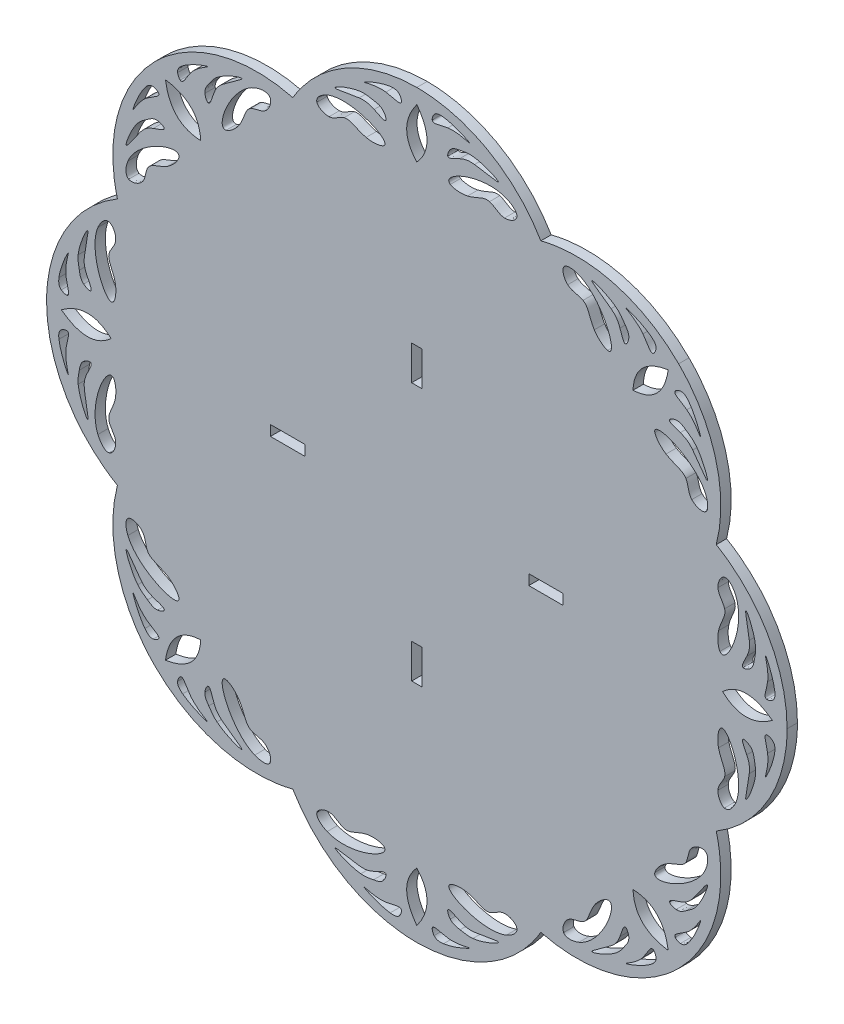
SolidWorks part; units mm, degrees
ref_plane "Plano frontal" through (0, 0, 0) normal (0, 0, 1) x (1, 0, 0)
ref_plane "Plano superior" through (0, 0, 0) normal (0, 1, 0) x (1, 0, 0)
ref_plane "Plano direito" through (0, 0, 0) normal (1, 0, 0) x (0, 0, -1)
sketch "Model" plane through (0, 0, 0) normal (0, 0, 1) x (1, 0, 0)
  line L0 (57.9546, 38.6366) -> (57.9546, 38.6367)
  line L37 (1, 34.3089) -> (1, 40.9756)
  line L38 (1, 40.9756) -> (-1, 40.9756)
  line L39 (-1, 40.9756) -> (-1, 34.3089)
  line L40 (-1, 34.3089) -> (1, 34.3089)
  line L41 (-21.6667, 63.6423) -> (-28.3333, 63.6423)
  line L42 (-28.3333, 63.6423) -> (-28.3333, 61.6423)
  line L43 (-28.3333, 61.6423) -> (-21.6667, 61.6423)
  line L44 (-21.6667, 61.6423) -> (-21.6667, 63.6423)
  line L45 (1, 84.3089) -> (1, 90.9756)
  line L46 (1, 90.9756) -> (-1, 90.9756)
  line L47 (-1, 90.9756) -> (-1, 84.3089)
  line L48 (-1, 84.3089) -> (1, 84.3089)
  line L49 (28.3333, 63.6423) -> (21.6667, 63.6423)
  line L50 (21.6667, 63.6423) -> (21.6667, 61.6423)
  line L51 (21.6667, 61.6423) -> (28.3333, 61.6423)
  line L52 (28.3333, 61.6423) -> (28.3333, 63.6423)
  spline S0 degree 3 poles (-52.251, 106.4004) (-51.0841, 107.3002) (-49.5495, 107.8231) (-50.0038, 108.419) knots 0 0 0 0 0.166667 0.166667 0.166667 0.166667
  spline S1 degree 3 poles (-50.0038, 108.419) (-50.1747, 108.6432) (-50.6272, 108.8778) (-51.0215, 108.9249) knots 0.166667 0.166667 0.166667 0.166667 0.333333 0.333333 0.333333 0.333333
  spline S2 degree 3 poles (-51.0215, 108.9249) (-51.675, 109.0029) (-52.169, 108.5658) (-52.6362, 107.9552) knots 0.333333 0.333333 0.333333 0.333333 0.5 0.5 0.5 0.5
  spline S3 degree 3 poles (-52.6362, 107.9552) (-53.9613, 106.2236) (-55.0715, 103.0965) (-54.9171, 103.125) knots 0.5 0.5 0.5 0.5 0.666667 0.666667 0.666667 0.666667
  spline S4 degree 3 poles (-54.9171, 103.125) (-54.795, 103.1474) (-53.8824, 105.1424) (-52.251, 106.4004) knots 0.666667 0.666667 0.666667 0.666667 1 1 1 1
  spline S5 degree 3 poles (-52.0754, 94.806) (-51.4239, 95.9147) (-49.6775, 96.0478) (-48.2286, 96.9769) knots 0 0 0 0 0.142857 0.142857 0.142857 0.142857
  spline S6 degree 3 poles (-48.2286, 96.9769) (-47.1297, 97.6816) (-46.2019, 98.8443) (-46.0577, 99.5288) knots 0.142857 0.142857 0.142857 0.142857 0.285714 0.285714 0.285714 0.285714
  spline S7 degree 3 poles (-46.0577, 99.5288) (-45.5709, 101.8383) (-54.0056, 98.7029) (-55.9222, 94.0062) knots 0.285714 0.285714 0.285714 0.285714 0.428571 0.428571 0.428571 0.428571
  spline S8 degree 3 poles (-55.9222, 94.0062) (-56.4255, 92.7729) (-56.4794, 91.4319) (-55.7669, 91.0417) knots 0.428571 0.428571 0.428571 0.428571 0.571429 0.571429 0.571429 0.571429
  spline S9 degree 3 poles (-55.7669, 91.0417) (-55.1261, 90.6907) (-53.8657, 91.1085) (-53.2181, 91.8352) knots 0.571429 0.571429 0.571429 0.571429 0.714286 0.714286 0.714286 0.714286
  spline S10 degree 3 poles (-53.2181, 91.8352) (-52.4459, 92.7016) (-52.5449, 94.007) (-52.0754, 94.806) knots 0.714286 0.714286 0.714286 0.714286 1 1 1 1
  spline S11 degree 3 poles (-32.1752, 114.7062) (-31.3763, 115.1757) (-30.0708, 115.0766) (-29.2044, 115.8488) knots 0 0 0 0 0.142857 0.142857 0.142857 0.142857
  spline S12 degree 3 poles (-29.2044, 115.8488) (-28.4777, 116.4964) (-28.0599, 117.757) (-28.4109, 118.3977) knots 0.142857 0.142857 0.142857 0.142857 0.285714 0.285714 0.285714 0.285714
  spline S13 degree 3 poles (-28.4109, 118.3977) (-28.8012, 119.1102) (-30.1421, 119.0563) (-31.3753, 118.553) knots 0.285714 0.285714 0.285714 0.285714 0.428571 0.428571 0.428571 0.428571
  spline S14 degree 3 poles (-31.3753, 118.553) (-36.0721, 116.6364) (-39.2076, 108.2017) (-36.898, 108.6885) knots 0.428571 0.428571 0.428571 0.428571 0.571429 0.571429 0.571429 0.571429
  spline S15 degree 3 poles (-36.898, 108.6885) (-36.2135, 108.8327) (-35.0509, 109.7605) (-34.3461, 110.8594) knots 0.571429 0.571429 0.571429 0.571429 0.714286 0.714286 0.714286 0.714286
  spline S16 degree 3 poles (-34.3461, 110.8594) (-33.417, 112.3083) (-33.2839, 114.0547) (-32.1752, 114.7062) knots 0.714286 0.714286 0.714286 0.714286 1 1 1 1
  spline S17 degree 3 poles (-43.7696, 114.8818) (-42.5116, 116.5132) (-40.5166, 117.4258) (-40.4942, 117.5479) knots 0 0 0 0 0.166667 0.166667 0.166667 0.166667
  spline S18 degree 3 poles (-40.4942, 117.5479) (-40.4657, 117.7023) (-43.5928, 116.5921) (-45.3244, 115.267) knots 0.166667 0.166667 0.166667 0.166667 0.333333 0.333333 0.333333 0.333333
  spline S19 degree 3 poles (-45.3244, 115.267) (-45.935, 114.7997) (-46.3721, 114.3058) (-46.2941, 113.6523) knots 0.333333 0.333333 0.333333 0.333333 0.5 0.5 0.5 0.5
  spline S20 degree 3 poles (-46.2941, 113.6523) (-46.247, 113.258) (-46.0124, 112.8056) (-45.7883, 112.6346) knots 0.5 0.5 0.5 0.5 0.666667 0.666667 0.666667 0.666667
  spline S21 degree 3 poles (-45.7883, 112.6346) (-45.1922, 112.1803) (-44.6694, 113.715) (-43.7696, 114.8818) knots 0.666667 0.666667 0.666667 0.666667 1 1 1 1
  spline S22 degree 3 poles (-65.3252, 54.2545) (-65.4688, 53.4561) (-65.6419, 52.7387) (-65.5496, 51.7858) knots 0 0 0 0 0.125 0.125 0.125 0.125
  spline S23 degree 3 poles (-65.5496, 51.7858) (-65.3525, 49.752) (-63.9461, 46.6455) (-63.6955, 46.8305) knots 0.125 0.125 0.125 0.125 0.25 0.25 0.25 0.25
  spline S24 degree 3 poles (-63.6955, 46.8305) (-63.4739, 46.9939) (-64.1556, 49.7294) (-64.3418, 51.4627) knots 0.25 0.25 0.25 0.25 0.375 0.375 0.375 0.375
  spline S25 degree 3 poles (-64.3418, 51.4627) (-64.4593, 52.5554) (-64.3798, 53.2498) (-63.8571, 54.3713) knots 0.375 0.375 0.375 0.375 0.5 0.5 0.5 0.5
  spline S26 degree 3 poles (-63.8571, 54.3713) (-63.4373, 55.272) (-62.7317, 56.4482) (-63.1569, 56.6336) knots 0.5 0.5 0.5 0.5 0.625 0.625 0.625 0.625
  spline S27 degree 3 poles (-63.1569, 56.6336) (-63.4116, 56.7446) (-64.0718, 56.5003) (-64.4916, 56.1539) knots 0.625 0.625 0.625 0.625 0.75 0.75 0.75 0.75
  spline S28 degree 3 poles (-64.4916, 56.1539) (-65.1055, 55.6473) (-65.205, 54.9225) (-65.3252, 54.2545) knots 0.75 0.75 0.75 0.75 1 1 1 1
  spline S29 degree 3 poles (-65.3252, 71.0071) (-65.205, 70.3391) (-65.1055, 69.6142) (-64.4916, 69.1077) knots 0 0 0 0 0.125 0.125 0.125 0.125
  spline S30 degree 3 poles (-64.4916, 69.1077) (-64.0718, 68.7613) (-63.4116, 68.517) (-63.1569, 68.628) knots 0.125 0.125 0.125 0.125 0.25 0.25 0.25 0.25
  spline S31 degree 3 poles (-63.1569, 68.628) (-62.7317, 68.8134) (-63.4373, 69.9896) (-63.8571, 70.8903) knots 0.25 0.25 0.25 0.25 0.375 0.375 0.375 0.375
  spline S32 degree 3 poles (-63.8571, 70.8903) (-64.3798, 72.0118) (-64.4593, 72.7061) (-64.3418, 73.7989) knots 0.375 0.375 0.375 0.375 0.5 0.5 0.5 0.5
  spline S33 degree 3 poles (-64.3418, 73.7989) (-64.1556, 75.5321) (-63.4739, 78.2676) (-63.6955, 78.4311) knots 0.5 0.5 0.5 0.5 0.625 0.625 0.625 0.625
  spline S34 degree 3 poles (-63.6955, 78.4311) (-63.9461, 78.616) (-65.3525, 75.5095) (-65.5496, 73.4757) knots 0.625 0.625 0.625 0.625 0.75 0.75 0.75 0.75
  spline S35 degree 3 poles (-65.5496, 73.4757) (-65.6419, 72.5229) (-65.4688, 71.8054) (-65.3252, 71.0071) knots 0.75 0.75 0.75 0.75 1 1 1 1
  spline S36 degree 3 poles (-43.7696, 10.3798) (-44.6694, 11.5466) (-45.1922, 13.0812) (-45.7883, 12.6269) knots 0 0 0 0 0.166667 0.166667 0.166667 0.166667
  spline S37 degree 3 poles (-45.7883, 12.6269) (-46.0124, 12.456) (-46.247, 12.0036) (-46.2941, 11.6093) knots 0.166667 0.166667 0.166667 0.166667 0.333333 0.333333 0.333333 0.333333
  spline S38 degree 3 poles (-46.2941, 11.6093) (-46.3721, 10.9558) (-45.935, 10.4618) (-45.3244, 9.9946) knots 0.333333 0.333333 0.333333 0.333333 0.5 0.5 0.5 0.5
  spline S39 degree 3 poles (-45.3244, 9.9946) (-43.5928, 8.6695) (-40.4657, 7.5593) (-40.4942, 7.7137) knots 0.5 0.5 0.5 0.5 0.666667 0.666667 0.666667 0.666667
  spline S40 degree 3 poles (-40.4942, 7.7137) (-40.5166, 7.8358) (-42.5116, 8.7484) (-43.7696, 10.3798) knots 0.666667 0.666667 0.666667 0.666667 1 1 1 1
  spline S41 degree 3 poles (-32.1752, 10.5553) (-33.2839, 11.2069) (-33.417, 12.9533) (-34.3461, 14.4022) knots 0 0 0 0 0.142857 0.142857 0.142857 0.142857
  spline S42 degree 3 poles (-34.3461, 14.4022) (-35.0509, 15.5011) (-36.2135, 16.4289) (-36.898, 16.5731) knots 0.142857 0.142857 0.142857 0.142857 0.285714 0.285714 0.285714 0.285714
  spline S43 degree 3 poles (-36.898, 16.5731) (-39.2076, 17.0598) (-36.0721, 8.6252) (-31.3753, 6.7085) knots 0.285714 0.285714 0.285714 0.285714 0.428571 0.428571 0.428571 0.428571
  spline S44 degree 3 poles (-31.3753, 6.7085) (-30.1421, 6.2053) (-28.8012, 6.1514) (-28.4109, 6.8639) knots 0.428571 0.428571 0.428571 0.428571 0.571429 0.571429 0.571429 0.571429
  spline S45 degree 3 poles (-28.4109, 6.8639) (-28.0599, 7.5046) (-28.4777, 8.7651) (-29.2044, 9.4128) knots 0.571429 0.571429 0.571429 0.571429 0.714286 0.714286 0.714286 0.714286
  spline S46 degree 3 poles (-29.2044, 9.4128) (-30.0708, 10.185) (-31.3763, 10.0859) (-32.1752, 10.5553) knots 0.714286 0.714286 0.714286 0.714286 1 1 1 1
  spline S47 degree 3 poles (-52.0754, 30.4556) (-52.5449, 31.2546) (-52.4459, 32.56) (-53.2181, 33.4264) knots 0 0 0 0 0.142857 0.142857 0.142857 0.142857
  spline S48 degree 3 poles (-53.2181, 33.4264) (-53.8657, 34.1531) (-55.1261, 34.5708) (-55.7669, 34.2199) knots 0.142857 0.142857 0.142857 0.142857 0.285714 0.285714 0.285714 0.285714
  spline S49 degree 3 poles (-55.7669, 34.2199) (-56.4794, 33.8296) (-56.4255, 32.4887) (-55.9222, 31.2554) knots 0.285714 0.285714 0.285714 0.285714 0.428571 0.428571 0.428571 0.428571
  spline S50 degree 3 poles (-55.9222, 31.2554) (-54.0056, 26.5587) (-45.5709, 23.4233) (-46.0577, 25.7328) knots 0.428571 0.428571 0.428571 0.428571 0.571429 0.571429 0.571429 0.571429
  spline S51 degree 3 poles (-46.0577, 25.7328) (-46.2019, 26.4173) (-47.1297, 27.5799) (-48.2286, 28.2847) knots 0.571429 0.571429 0.571429 0.571429 0.714286 0.714286 0.714286 0.714286
  spline S52 degree 3 poles (-48.2286, 28.2847) (-49.6775, 29.2138) (-51.4239, 29.3469) (-52.0754, 30.4556) knots 0.714286 0.714286 0.714286 0.714286 1 1 1 1
  spline S53 degree 3 poles (-52.251, 18.8612) (-53.8824, 20.1192) (-54.795, 22.1142) (-54.9171, 22.1366) knots 0 0 0 0 0.166667 0.166667 0.166667 0.166667
  spline S54 degree 3 poles (-54.9171, 22.1366) (-55.0715, 22.1651) (-53.9613, 19.038) (-52.6362, 17.3064) knots 0.166667 0.166667 0.166667 0.166667 0.333333 0.333333 0.333333 0.333333
  spline S55 degree 3 poles (-52.6362, 17.3064) (-52.169, 16.6958) (-51.675, 16.2587) (-51.0215, 16.3367) knots 0.333333 0.333333 0.333333 0.333333 0.5 0.5 0.5 0.5
  spline S56 degree 3 poles (-51.0215, 16.3367) (-50.6272, 16.3838) (-50.1747, 16.6183) (-50.0038, 16.8425) knots 0.5 0.5 0.5 0.5 0.666667 0.666667 0.666667 0.666667
  spline S57 degree 3 poles (-50.0038, 16.8425) (-49.5495, 17.4385) (-51.0841, 17.9613) (-52.251, 18.8612) knots 0.666667 0.666667 0.666667 0.666667 1 1 1 1
  spline S58 degree 3 poles (8.3763, -2.6943) (9.1746, -2.838) (9.8921, -3.0111) (10.8449, -2.9188) knots 0 0 0 0 0.125 0.125 0.125 0.125
  spline S59 degree 3 poles (10.8449, -2.9188) (12.8788, -2.7217) (15.9852, -1.3154) (15.8003, -1.0647) knots 0.125 0.125 0.125 0.125 0.25 0.25 0.25 0.25
  spline S60 degree 3 poles (15.8003, -1.0647) (15.6369, -0.8432) (12.9013, -1.5248) (11.1681, -1.711) knots 0.25 0.25 0.25 0.25 0.375 0.375 0.375 0.375
  spline S61 degree 3 poles (11.1681, -1.711) (10.0754, -1.8285) (9.381, -1.749) (8.2594, -1.2263) knots 0.375 0.375 0.375 0.375 0.5 0.5 0.5 0.5
  spline S62 degree 3 poles (8.2594, -1.2263) (7.3588, -0.8065) (6.1826, -0.1009) (5.9972, -0.5261) knots 0.5 0.5 0.5 0.5 0.625 0.625 0.625 0.625
  spline S63 degree 3 poles (5.9972, -0.5261) (5.8862, -0.7807) (6.1305, -1.441) (6.4769, -1.8608) knots 0.625 0.625 0.625 0.625 0.75 0.75 0.75 0.75
  spline S64 degree 3 poles (6.4769, -1.8608) (6.9834, -2.4747) (7.7082, -2.5742) (8.3763, -2.6943) knots 0.75 0.75 0.75 0.75 1 1 1 1
  spline S65 degree 3 poles (-8.3763, -2.6943) (-7.7083, -2.5742) (-6.9834, -2.4747) (-6.4769, -1.8608) knots 0 0 0 0 0.125 0.125 0.125 0.125
  spline S66 degree 3 poles (-6.4769, -1.8608) (-6.1305, -1.441) (-5.8862, -0.7807) (-5.9972, -0.5261) knots 0.125 0.125 0.125 0.125 0.25 0.25 0.25 0.25
  spline S67 degree 3 poles (-5.9972, -0.5261) (-6.1826, -0.1009) (-7.3588, -0.8065) (-8.2595, -1.2263) knots 0.25 0.25 0.25 0.25 0.375 0.375 0.375 0.375
  spline S68 degree 3 poles (-8.2595, -1.2263) (-9.381, -1.749) (-10.0754, -1.8285) (-11.1681, -1.711) knots 0.375 0.375 0.375 0.375 0.5 0.5 0.5 0.5
  spline S69 degree 3 poles (-11.1681, -1.711) (-12.9013, -1.5248) (-15.6369, -0.8432) (-15.8004, -1.0647) knots 0.5 0.5 0.5 0.5 0.625 0.625 0.625 0.625
  spline S70 degree 3 poles (-15.8004, -1.0647) (-15.9853, -1.3154) (-12.8788, -2.7217) (-10.845, -2.9188) knots 0.625 0.625 0.625 0.625 0.75 0.75 0.75 0.75
  spline S71 degree 3 poles (-10.845, -2.9188) (-9.8921, -3.0111) (-9.1746, -2.838) (-8.3763, -2.6943) knots 0.75 0.75 0.75 0.75 1 1 1 1
  spline S72 degree 3 poles (52.251, 18.8612) (51.0842, 17.9613) (49.5495, 17.4385) (50.0038, 16.8425) knots 0 0 0 0 0.166667 0.166667 0.166667 0.166667
  spline S73 degree 3 poles (50.0038, 16.8425) (50.1747, 16.6183) (50.6272, 16.3838) (51.0215, 16.3367) knots 0.166667 0.166667 0.166667 0.166667 0.333333 0.333333 0.333333 0.333333
  spline S74 degree 3 poles (51.0215, 16.3367) (51.675, 16.2587) (52.169, 16.6958) (52.6362, 17.3064) knots 0.333333 0.333333 0.333333 0.333333 0.5 0.5 0.5 0.5
  spline S75 degree 3 poles (52.6362, 17.3064) (53.9612, 19.038) (55.0715, 22.1651) (54.9171, 22.1366) knots 0.5 0.5 0.5 0.5 0.666667 0.666667 0.666667 0.666667
  spline S76 degree 3 poles (54.9171, 22.1366) (54.795, 22.1142) (53.8824, 20.1192) (52.251, 18.8612) knots 0.666667 0.666667 0.666667 0.666667 1 1 1 1
  spline S77 degree 3 poles (52.0754, 30.4556) (51.4239, 29.3469) (49.6775, 29.2138) (48.2286, 28.2847) knots 0 0 0 0 0.142857 0.142857 0.142857 0.142857
  spline S78 degree 3 poles (48.2286, 28.2847) (47.1297, 27.5799) (46.2019, 26.4173) (46.0577, 25.7328) knots 0.142857 0.142857 0.142857 0.142857 0.285714 0.285714 0.285714 0.285714
  spline S79 degree 3 poles (46.0577, 25.7328) (45.5709, 23.4233) (54.0056, 26.5587) (55.9222, 31.2554) knots 0.285714 0.285714 0.285714 0.285714 0.428571 0.428571 0.428571 0.428571
  spline S80 degree 3 poles (55.9222, 31.2554) (56.4255, 32.4887) (56.4794, 33.8296) (55.7669, 34.2199) knots 0.428571 0.428571 0.428571 0.428571 0.571429 0.571429 0.571429 0.571429
  spline S81 degree 3 poles (55.7669, 34.2199) (55.1262, 34.5708) (53.8657, 34.1531) (53.218, 33.4264) knots 0.571429 0.571429 0.571429 0.571429 0.714286 0.714286 0.714286 0.714286
  spline S82 degree 3 poles (53.218, 33.4264) (52.4458, 32.56) (52.5449, 31.2546) (52.0754, 30.4556) knots 0.714286 0.714286 0.714286 0.714286 1 1 1 1
  spline S83 degree 3 poles (32.1751, 10.5553) (31.3762, 10.0859) (30.0708, 10.185) (29.2043, 9.4128) knots 0 0 0 0 0.142857 0.142857 0.142857 0.142857
  spline S84 degree 3 poles (29.2043, 9.4128) (28.4777, 8.7651) (28.0599, 7.5046) (28.4109, 6.8639) knots 0.142857 0.142857 0.142857 0.142857 0.285714 0.285714 0.285714 0.285714
  spline S85 degree 3 poles (28.4109, 6.8639) (28.8012, 6.1514) (30.1421, 6.2053) (31.3753, 6.7085) knots 0.285714 0.285714 0.285714 0.285714 0.428571 0.428571 0.428571 0.428571
  spline S86 degree 3 poles (31.3753, 6.7085) (36.0721, 8.6252) (39.2075, 17.0598) (36.8979, 16.5731) knots 0.428571 0.428571 0.428571 0.428571 0.571429 0.571429 0.571429 0.571429
  spline S87 degree 3 poles (36.8979, 16.5731) (36.2135, 16.4289) (35.0509, 15.5011) (34.3461, 14.4022) knots 0.571429 0.571429 0.571429 0.571429 0.714286 0.714286 0.714286 0.714286
  spline S88 degree 3 poles (34.3461, 14.4022) (33.417, 12.9533) (33.2838, 11.2069) (32.1751, 10.5553) knots 0.714286 0.714286 0.714286 0.714286 1 1 1 1
  spline S89 degree 3 poles (43.7696, 10.3798) (42.5116, 8.7484) (40.5166, 7.8358) (40.4941, 7.7137) knots 0 0 0 0 0.166667 0.166667 0.166667 0.166667
  spline S90 degree 3 poles (40.4941, 7.7137) (40.4657, 7.5593) (43.5927, 8.6695) (45.3244, 9.9946) knots 0.166667 0.166667 0.166667 0.166667 0.333333 0.333333 0.333333 0.333333
  spline S91 degree 3 poles (45.3244, 9.9946) (45.9349, 10.4618) (46.3721, 10.9558) (46.2941, 11.6093) knots 0.333333 0.333333 0.333333 0.333333 0.5 0.5 0.5 0.5
  spline S92 degree 3 poles (46.2941, 11.6093) (46.247, 12.0036) (46.0124, 12.456) (45.7882, 12.6269) knots 0.5 0.5 0.5 0.5 0.666667 0.666667 0.666667 0.666667
  spline S93 degree 3 poles (45.7882, 12.6269) (45.1922, 13.0812) (44.6694, 11.5466) (43.7696, 10.3798) knots 0.666667 0.666667 0.666667 0.666667 1 1 1 1
  spline S94 degree 3 poles (65.3252, 71.0071) (65.4688, 71.8054) (65.6419, 72.5229) (65.5496, 73.4757) knots 0 0 0 0 0.125 0.125 0.125 0.125
  spline S95 degree 3 poles (65.5496, 73.4757) (65.3525, 75.5095) (63.9461, 78.616) (63.6955, 78.4311) knots 0.125 0.125 0.125 0.125 0.25 0.25 0.25 0.25
  spline S96 degree 3 poles (63.6955, 78.4311) (63.4739, 78.2676) (64.1556, 75.5321) (64.3418, 73.7989) knots 0.25 0.25 0.25 0.25 0.375 0.375 0.375 0.375
  spline S97 degree 3 poles (64.3418, 73.7989) (64.4593, 72.7061) (64.3798, 72.0118) (63.8571, 70.8903) knots 0.375 0.375 0.375 0.375 0.5 0.5 0.5 0.5
  spline S98 degree 3 poles (63.8571, 70.8903) (63.4373, 69.9896) (62.7316, 68.8134) (63.1568, 68.628) knots 0.5 0.5 0.5 0.5 0.625 0.625 0.625 0.625
  spline S99 degree 3 poles (63.1568, 68.628) (63.4115, 68.517) (64.0718, 68.7613) (64.4916, 69.1077) knots 0.625 0.625 0.625 0.625 0.75 0.75 0.75 0.75
  spline S100 degree 3 poles (64.4916, 69.1077) (65.1055, 69.6142) (65.205, 70.3391) (65.3252, 71.0071) knots 0.75 0.75 0.75 0.75 1 1 1 1
  spline S101 degree 3 poles (65.3252, 54.2545) (65.205, 54.9225) (65.1055, 55.6473) (64.4916, 56.1539) knots 0 0 0 0 0.125 0.125 0.125 0.125
  spline S102 degree 3 poles (64.4916, 56.1539) (64.0718, 56.5003) (63.4115, 56.7446) (63.1568, 56.6336) knots 0.125 0.125 0.125 0.125 0.25 0.25 0.25 0.25
  spline S103 degree 3 poles (63.1568, 56.6336) (62.7316, 56.4482) (63.4373, 55.272) (63.8571, 54.3713) knots 0.25 0.25 0.25 0.25 0.375 0.375 0.375 0.375
  spline S104 degree 3 poles (63.8571, 54.3713) (64.3798, 53.2498) (64.4593, 52.5554) (64.3418, 51.4627) knots 0.375 0.375 0.375 0.375 0.5 0.5 0.5 0.5
  spline S105 degree 3 poles (64.3418, 51.4627) (64.1556, 49.7294) (63.4739, 46.9939) (63.6955, 46.8305) knots 0.5 0.5 0.5 0.5 0.625 0.625 0.625 0.625
  spline S106 degree 3 poles (63.6955, 46.8305) (63.9461, 46.6455) (65.3525, 49.752) (65.5496, 51.7858) knots 0.625 0.625 0.625 0.625 0.75 0.75 0.75 0.75
  spline S107 degree 3 poles (65.5496, 51.7858) (65.6419, 52.7387) (65.4688, 53.4561) (65.3252, 54.2545) knots 0.75 0.75 0.75 0.75 1 1 1 1
  spline S108 degree 3 poles (43.7696, 114.8818) (44.6694, 113.715) (45.1922, 112.1803) (45.7882, 112.6346) knots 0 0 0 0 0.166667 0.166667 0.166667 0.166667
  spline S109 degree 3 poles (45.7882, 112.6346) (46.0124, 112.8056) (46.247, 113.258) (46.2941, 113.6523) knots 0.166667 0.166667 0.166667 0.166667 0.333333 0.333333 0.333333 0.333333
  spline S110 degree 3 poles (46.2941, 113.6523) (46.3721, 114.3058) (45.9349, 114.7997) (45.3244, 115.267) knots 0.333333 0.333333 0.333333 0.333333 0.5 0.5 0.5 0.5
  spline S111 degree 3 poles (45.3244, 115.267) (43.5927, 116.5921) (40.4657, 117.7023) (40.4941, 117.5479) knots 0.5 0.5 0.5 0.5 0.666667 0.666667 0.666667 0.666667
  spline S112 degree 3 poles (40.4941, 117.5479) (40.5166, 117.4258) (42.5116, 116.5132) (43.7696, 114.8818) knots 0.666667 0.666667 0.666667 0.666667 1 1 1 1
  spline S113 degree 3 poles (32.1751, 114.7062) (33.2838, 114.0547) (33.417, 112.3083) (34.3461, 110.8594) knots 0 0 0 0 0.142857 0.142857 0.142857 0.142857
  spline S114 degree 3 poles (34.3461, 110.8594) (35.0509, 109.7605) (36.2135, 108.8327) (36.8979, 108.6885) knots 0.142857 0.142857 0.142857 0.142857 0.285714 0.285714 0.285714 0.285714
  spline S115 degree 3 poles (36.8979, 108.6885) (39.2075, 108.2017) (36.0721, 116.6364) (31.3753, 118.553) knots 0.285714 0.285714 0.285714 0.285714 0.428571 0.428571 0.428571 0.428571
  spline S116 degree 3 poles (31.3753, 118.553) (30.1421, 119.0563) (28.8012, 119.1102) (28.4109, 118.3977) knots 0.428571 0.428571 0.428571 0.428571 0.571429 0.571429 0.571429 0.571429
  spline S117 degree 3 poles (28.4109, 118.3977) (28.0599, 117.757) (28.4777, 116.4964) (29.2043, 115.8488) knots 0.571429 0.571429 0.571429 0.571429 0.714286 0.714286 0.714286 0.714286
  spline S118 degree 3 poles (29.2043, 115.8488) (30.0708, 115.0766) (31.3762, 115.1757) (32.1751, 114.7062) knots 0.714286 0.714286 0.714286 0.714286 1 1 1 1
  spline S119 degree 3 poles (52.0754, 94.806) (52.5449, 94.007) (52.4458, 92.7016) (53.218, 91.8352) knots 0 0 0 0 0.142857 0.142857 0.142857 0.142857
  spline S120 degree 3 poles (53.218, 91.8352) (53.8657, 91.1085) (55.1262, 90.6907) (55.7669, 91.0417) knots 0.142857 0.142857 0.142857 0.142857 0.285714 0.285714 0.285714 0.285714
  spline S121 degree 3 poles (55.7669, 91.0417) (56.4794, 91.4319) (56.4255, 92.7729) (55.9222, 94.0062) knots 0.285714 0.285714 0.285714 0.285714 0.428571 0.428571 0.428571 0.428571
  spline S122 degree 3 poles (55.9222, 94.0062) (54.0056, 98.7029) (45.5709, 101.8383) (46.0577, 99.5288) knots 0.428571 0.428571 0.428571 0.428571 0.571429 0.571429 0.571429 0.571429
  spline S123 degree 3 poles (46.0577, 99.5288) (46.2019, 98.8443) (47.1297, 97.6816) (48.2286, 96.9769) knots 0.571429 0.571429 0.571429 0.571429 0.714286 0.714286 0.714286 0.714286
  spline S124 degree 3 poles (48.2286, 96.9769) (49.6775, 96.0478) (51.4239, 95.9147) (52.0754, 94.806) knots 0.714286 0.714286 0.714286 0.714286 1 1 1 1
  spline S125 degree 3 poles (52.251, 106.4004) (53.8824, 105.1424) (54.795, 103.1474) (54.9171, 103.125) knots 0 0 0 0 0.166667 0.166667 0.166667 0.166667
  spline S126 degree 3 poles (54.9171, 103.125) (55.0715, 103.0965) (53.9612, 106.2236) (52.6362, 107.9552) knots 0.166667 0.166667 0.166667 0.166667 0.333333 0.333333 0.333333 0.333333
  spline S127 degree 3 poles (52.6362, 107.9552) (52.169, 108.5658) (51.675, 109.0029) (51.0215, 108.9249) knots 0.333333 0.333333 0.333333 0.333333 0.5 0.5 0.5 0.5
  spline S128 degree 3 poles (51.0215, 108.9249) (50.6272, 108.8778) (50.1747, 108.6432) (50.0038, 108.419) knots 0.5 0.5 0.5 0.5 0.666667 0.666667 0.666667 0.666667
  spline S129 degree 3 poles (50.0038, 108.419) (49.5495, 107.8231) (51.0842, 107.3002) (52.251, 106.4004) knots 0.666667 0.666667 0.666667 0.666667 1 1 1 1
  spline S130 degree 3 poles (-8.3763, 127.9559) (-9.1746, 128.0996) (-9.8921, 128.2727) (-10.845, 128.1804) knots 0 0 0 0 0.125 0.125 0.125 0.125
  spline S131 degree 3 poles (-10.845, 128.1804) (-12.8788, 127.9833) (-15.9853, 126.5769) (-15.8004, 126.3263) knots 0.125 0.125 0.125 0.125 0.25 0.25 0.25 0.25
  spline S132 degree 3 poles (-15.8004, 126.3263) (-15.6369, 126.1047) (-12.9013, 126.7864) (-11.1681, 126.9726) knots 0.25 0.25 0.25 0.25 0.375 0.375 0.375 0.375
  spline S133 degree 3 poles (-11.1681, 126.9726) (-10.0754, 127.0901) (-9.381, 127.0106) (-8.2595, 126.4879) knots 0.375 0.375 0.375 0.375 0.5 0.5 0.5 0.5
  spline S134 degree 3 poles (-8.2595, 126.4879) (-7.3588, 126.0681) (-6.1826, 125.3625) (-5.9972, 125.7876) knots 0.5 0.5 0.5 0.5 0.625 0.625 0.625 0.625
  spline S135 degree 3 poles (-5.9972, 125.7876) (-5.8862, 126.0423) (-6.1305, 126.7026) (-6.4769, 127.1224) knots 0.625 0.625 0.625 0.625 0.75 0.75 0.75 0.75
  spline S136 degree 3 poles (-6.4769, 127.1224) (-6.9834, 127.7363) (-7.7083, 127.8358) (-8.3763, 127.9559) knots 0.75 0.75 0.75 0.75 1 1 1 1
  spline S137 degree 3 poles (8.3763, 127.9559) (7.7082, 127.8358) (6.9834, 127.7363) (6.4769, 127.1224) knots 0 0 0 0 0.125 0.125 0.125 0.125
  spline S138 degree 3 poles (6.4769, 127.1224) (6.1305, 126.7026) (5.8862, 126.0423) (5.9972, 125.7876) knots 0.125 0.125 0.125 0.125 0.25 0.25 0.25 0.25
  spline S139 degree 3 poles (5.9972, 125.7876) (6.1826, 125.3625) (7.3588, 126.0681) (8.2594, 126.4879) knots 0.25 0.25 0.25 0.25 0.375 0.375 0.375 0.375
  spline S140 degree 3 poles (8.2594, 126.4879) (9.381, 127.0106) (10.0754, 127.0901) (11.1681, 126.9726) knots 0.375 0.375 0.375 0.375 0.5 0.5 0.5 0.5
  spline S141 degree 3 poles (11.1681, 126.9726) (12.9013, 126.7864) (15.6369, 126.1047) (15.8003, 126.3263) knots 0.5 0.5 0.5 0.5 0.625 0.625 0.625 0.625
  spline S142 degree 3 poles (15.8003, 126.3263) (15.9852, 126.5769) (12.8788, 127.9833) (10.8449, 128.1804) knots 0.625 0.625 0.625 0.625 0.75 0.75 0.75 0.75
  spline S143 degree 3 poles (10.8449, 128.1804) (9.8921, 128.2727) (9.1746, 128.0996) (8.3763, 127.9559) knots 0.75 0.75 0.75 0.75 1 1 1 1
  spline S144 degree 3 poles (5.9972, 130.5276) (8.0404, 130.7916) (10.0963, 130.0262) (10.1985, 130.0967) knots 0 0 0 0 0.166667 0.166667 0.166667 0.166667
  spline S145 degree 3 poles (10.1985, 130.0967) (10.3278, 130.1858) (7.3317, 131.6119) (5.1702, 131.8994) knots 0.166667 0.166667 0.166667 0.166667 0.333333 0.333333 0.333333 0.333333
  spline S146 degree 3 poles (5.1702, 131.8994) (4.4081, 132.0008) (3.7497, 131.9605) (3.3427, 131.4433) knots 0.333333 0.333333 0.333333 0.333333 0.5 0.5 0.5 0.5
  spline S147 degree 3 poles (3.3427, 131.4433) (3.0972, 131.1312) (2.9432, 130.6454) (2.9809, 130.366) knots 0.5 0.5 0.5 0.5 0.666667 0.666667 0.666667 0.666667
  spline S148 degree 3 poles (2.9809, 130.366) (3.0811, 129.6234) (4.5359, 130.3388) (5.9972, 130.5276) knots 0.666667 0.666667 0.666667 0.666667 1 1 1 1
  spline S149 degree 3 poles (14.0716, 122.205) (14.9685, 121.972) (15.8216, 120.9788) (16.9802, 120.9123) knots 0 0 0 0 0.142857 0.142857 0.142857 0.142857
  spline S150 degree 3 poles (16.9802, 120.9123) (17.952, 120.8564) (19.1387, 121.4522) (19.3436, 122.1535) knots 0.142857 0.142857 0.142857 0.142857 0.285714 0.285714 0.285714 0.285714
  spline S151 degree 3 poles (19.3436, 122.1535) (19.5715, 122.9333) (18.5852, 123.8433) (17.3573, 124.3595) knots 0.285714 0.285714 0.285714 0.285714 0.428571 0.428571 0.428571 0.428571
  spline S152 degree 3 poles (17.3573, 124.3595) (12.6809, 126.3253) (4.4996, 122.5782) (6.4769, 121.2893) knots 0.428571 0.428571 0.428571 0.428571 0.571429 0.571429 0.571429 0.571429
  spline S153 degree 3 poles (6.4769, 121.2893) (7.0629, 120.9073) (8.541, 120.7412) (9.8164, 121.02) knots 0.571429 0.571429 0.571429 0.571429 0.714286 0.714286 0.714286 0.714286
  spline S154 degree 3 poles (9.8164, 121.02) (11.4979, 121.3875) (12.8269, 122.5282) (14.0716, 122.205) knots 0.714286 0.714286 0.714286 0.714286 1 1 1 1
  spline S155 degree 3 poles (-14.0716, 122.205) (-12.827, 122.5282) (-11.4979, 121.3875) (-9.8164, 121.02) knots 0 0 0 0 0.142857 0.142857 0.142857 0.142857
  spline S156 degree 3 poles (-9.8164, 121.02) (-8.5411, 120.7412) (-7.0629, 120.9073) (-6.4769, 121.2893) knots 0.142857 0.142857 0.142857 0.142857 0.285714 0.285714 0.285714 0.285714
  spline S157 degree 3 poles (-6.4769, 121.2893) (-4.4996, 122.5782) (-12.6809, 126.3253) (-17.3573, 124.3595) knots 0.285714 0.285714 0.285714 0.285714 0.428571 0.428571 0.428571 0.428571
  spline S158 degree 3 poles (-17.3573, 124.3595) (-18.5852, 123.8433) (-19.5715, 122.9333) (-19.3436, 122.1535) knots 0.428571 0.428571 0.428571 0.428571 0.571429 0.571429 0.571429 0.571429
  spline S159 degree 3 poles (-19.3436, 122.1535) (-19.1388, 121.4522) (-17.952, 120.8564) (-16.9802, 120.9123) knots 0.571429 0.571429 0.571429 0.571429 0.714286 0.714286 0.714286 0.714286
  spline S160 degree 3 poles (-16.9802, 120.9123) (-15.8216, 120.9788) (-14.9685, 121.972) (-14.0716, 122.205) knots 0.714286 0.714286 0.714286 0.714286 1 1 1 1
  spline S161 degree 3 poles (-5.9972, 130.5276) (-4.5359, 130.3388) (-3.0811, 129.6234) (-2.9809, 130.366) knots 0 0 0 0 0.166667 0.166667 0.166667 0.166667
  spline S162 degree 3 poles (-2.9809, 130.366) (-2.9432, 130.6454) (-3.0973, 131.1312) (-3.3428, 131.4433) knots 0.166667 0.166667 0.166667 0.166667 0.333333 0.333333 0.333333 0.333333
  spline S163 degree 3 poles (-3.3428, 131.4433) (-3.7498, 131.9605) (-4.4081, 132.0008) (-5.1702, 131.8994) knots 0.333333 0.333333 0.333333 0.333333 0.5 0.5 0.5 0.5
  spline S164 degree 3 poles (-5.1702, 131.8994) (-7.3317, 131.6119) (-10.3278, 130.1858) (-10.1986, 130.0967) knots 0.5 0.5 0.5 0.5 0.666667 0.666667 0.666667 0.666667
  spline S165 degree 3 poles (-10.1986, 130.0967) (-10.0963, 130.0262) (-8.0405, 130.7916) (-5.9972, 130.5276) knots 0.666667 0.666667 0.666667 0.666667 1 1 1 1
  spline S166 degree 3 poles (52.1148, 102.8997) (51.5575, 103.2871) (50.9745, 103.7293) (50.1823, 103.6534) knots 0 0 0 0 0.125 0.125 0.125 0.125
  spline S167 degree 3 poles (50.1823, 103.6534) (49.6405, 103.6014) (49.0008, 103.3074) (48.8993, 103.0488) knots 0.125 0.125 0.125 0.125 0.25 0.25 0.25 0.25
  spline S168 degree 3 poles (48.8993, 103.0488) (48.7297, 102.617) (50.0604, 102.2843) (50.9941, 101.9442) knots 0.25 0.25 0.25 0.25 0.375 0.375 0.375 0.375
  spline S169 degree 3 poles (50.9941, 101.9442) (52.1567, 101.5209) (52.7039, 101.086) (53.3936, 100.2303) knots 0.375 0.375 0.375 0.375 0.5 0.5 0.5 0.5
  spline S170 degree 3 poles (53.3936, 100.2303) (54.4875, 98.873) (55.9398, 96.4567) (56.212, 96.4978) knots 0.5 0.5 0.5 0.5 0.625 0.625 0.625 0.625
  spline S171 degree 3 poles (56.212, 96.4978) (56.52, 96.5443) (55.3179, 99.7353) (54.0191, 101.3128) knots 0.625 0.625 0.625 0.625 0.75 0.75 0.75 0.75
  spline S172 degree 3 poles (54.0191, 101.3128) (53.4106, 102.0519) (52.7809, 102.4368) (52.1148, 102.8997) knots 0.75 0.75 0.75 0.75 1 1 1 1
  spline S173 degree 3 poles (40.2689, 114.7456) (39.8059, 115.4117) (39.4211, 116.0414) (38.682, 116.6499) knots 0 0 0 0 0.125 0.125 0.125 0.125
  spline S174 degree 3 poles (38.682, 116.6499) (37.1045, 117.9487) (33.9135, 119.1508) (33.867, 118.8428) knots 0.125 0.125 0.125 0.125 0.25 0.25 0.25 0.25
  spline S175 degree 3 poles (33.867, 118.8428) (33.8259, 118.5706) (36.2422, 117.1183) (37.5995, 116.0244) knots 0.25 0.25 0.25 0.25 0.375 0.375 0.375 0.375
  spline S176 degree 3 poles (37.5995, 116.0244) (38.4552, 115.3347) (38.89, 114.7875) (39.3134, 113.6249) knots 0.375 0.375 0.375 0.375 0.5 0.5 0.5 0.5
  spline S177 degree 3 poles (39.3134, 113.6249) (39.6535, 112.6912) (39.9862, 111.3606) (40.418, 111.5301) knots 0.5 0.5 0.5 0.5 0.625 0.625 0.625 0.625
  spline S178 degree 3 poles (40.418, 111.5301) (40.6765, 111.6317) (40.9707, 112.2713) (41.0226, 112.8131) knots 0.625 0.625 0.625 0.625 0.75 0.75 0.75 0.75
  spline S179 degree 3 poles (41.0226, 112.8131) (41.0985, 113.6054) (40.6563, 114.1882) (40.2689, 114.7456) knots 0.75 0.75 0.75 0.75 1 1 1 1
  spline S180 degree 3 poles (67.8968, 56.6336) (68.1609, 54.5904) (67.3955, 52.5344) (67.4659, 52.4322) knots 0 0 0 0 0.166667 0.166667 0.166667 0.166667
  spline S181 degree 3 poles (67.4659, 52.4322) (67.555, 52.303) (68.9811, 55.2991) (69.2686, 57.4606) knots 0.166667 0.166667 0.166667 0.166667 0.333333 0.333333 0.333333 0.333333
  spline S182 degree 3 poles (69.2686, 57.4606) (69.3699, 58.2227) (69.3298, 58.881) (68.8125, 59.2881) knots 0.333333 0.333333 0.333333 0.333333 0.5 0.5 0.5 0.5
  spline S183 degree 3 poles (68.8125, 59.2881) (68.5004, 59.5335) (68.0147, 59.6876) (67.7352, 59.6499) knots 0.5 0.5 0.5 0.5 0.666667 0.666667 0.666667 0.666667
  spline S184 degree 3 poles (67.7352, 59.6499) (66.9926, 59.5497) (67.708, 58.0949) (67.8968, 56.6336) knots 0.666667 0.666667 0.666667 0.666667 1 1 1 1
  spline S185 degree 3 poles (59.5742, 48.5592) (59.3412, 47.6623) (58.3481, 46.8092) (58.2814, 45.6505) knots 0 0 0 0 0.142857 0.142857 0.142857 0.142857
  spline S186 degree 3 poles (58.2814, 45.6505) (58.2256, 44.6788) (58.8214, 43.492) (59.5227, 43.2871) knots 0.142857 0.142857 0.142857 0.142857 0.285714 0.285714 0.285714 0.285714
  spline S187 degree 3 poles (59.5227, 43.2871) (60.3024, 43.0593) (61.2125, 44.0456) (61.7287, 45.2735) knots 0.285714 0.285714 0.285714 0.285714 0.428571 0.428571 0.428571 0.428571
  spline S188 degree 3 poles (61.7287, 45.2735) (63.6945, 49.9499) (59.9474, 58.1312) (58.6585, 56.1539) knots 0.428571 0.428571 0.428571 0.428571 0.571429 0.571429 0.571429 0.571429
  spline S189 degree 3 poles (58.6585, 56.1539) (58.2765, 55.5679) (58.1104, 54.0897) (58.3892, 52.8144) knots 0.571429 0.571429 0.571429 0.571429 0.714286 0.714286 0.714286 0.714286
  spline S190 degree 3 poles (58.3892, 52.8144) (58.7567, 51.1328) (59.8974, 49.8038) (59.5742, 48.5592) knots 0.714286 0.714286 0.714286 0.714286 1 1 1 1
  spline S191 degree 3 poles (59.5742, 76.7024) (59.8974, 75.4577) (58.7567, 74.1287) (58.3892, 72.4472) knots 0 0 0 0 0.142857 0.142857 0.142857 0.142857
  spline S192 degree 3 poles (58.3892, 72.4472) (58.1104, 71.1719) (58.2765, 69.6937) (58.6585, 69.1077) knots 0.142857 0.142857 0.142857 0.142857 0.285714 0.285714 0.285714 0.285714
  spline S193 degree 3 poles (58.6585, 69.1077) (59.9474, 67.1304) (63.6945, 75.3117) (61.7287, 79.9881) knots 0.285714 0.285714 0.285714 0.285714 0.428571 0.428571 0.428571 0.428571
  spline S194 degree 3 poles (61.7287, 79.9881) (61.2125, 81.216) (60.3024, 82.2023) (59.5227, 81.9744) knots 0.428571 0.428571 0.428571 0.428571 0.571429 0.571429 0.571429 0.571429
  spline S195 degree 3 poles (59.5227, 81.9744) (58.8214, 81.7695) (58.2256, 80.5828) (58.2814, 79.611) knots 0.571429 0.571429 0.571429 0.571429 0.714286 0.714286 0.714286 0.714286
  spline S196 degree 3 poles (58.2814, 79.611) (58.3481, 78.4523) (59.3412, 77.5993) (59.5742, 76.7024) knots 0.714286 0.714286 0.714286 0.714286 1 1 1 1
  spline S197 degree 3 poles (67.8968, 68.628) (67.708, 67.1667) (66.9926, 65.7119) (67.7352, 65.6117) knots 0 0 0 0 0.166667 0.166667 0.166667 0.166667
  spline S198 degree 3 poles (67.7352, 65.6117) (68.0147, 65.574) (68.5004, 65.7281) (68.8125, 65.9735) knots 0.166667 0.166667 0.166667 0.166667 0.333333 0.333333 0.333333 0.333333
  spline S199 degree 3 poles (68.8125, 65.9735) (69.3298, 66.3805) (69.3699, 67.0389) (69.2686, 67.801) knots 0.333333 0.333333 0.333333 0.333333 0.5 0.5 0.5 0.5
  spline S200 degree 3 poles (69.2686, 67.801) (68.9811, 69.9625) (67.555, 72.9586) (67.4659, 72.8293) knots 0.5 0.5 0.5 0.5 0.666667 0.666667 0.666667 0.666667
  spline S201 degree 3 poles (67.4659, 72.8293) (67.3955, 72.7271) (68.1609, 70.6712) (67.8968, 68.628) knots 0.666667 0.666667 0.666667 0.666667 1 1 1 1
  spline S202 degree 3 poles (40.2689, 10.516) (40.6563, 11.0733) (41.0985, 11.6562) (41.0226, 12.4485) knots 0 0 0 0 0.125 0.125 0.125 0.125
  spline S203 degree 3 poles (41.0226, 12.4485) (40.9707, 12.9902) (40.6765, 13.6299) (40.418, 13.7314) knots 0.125 0.125 0.125 0.125 0.25 0.25 0.25 0.25
  spline S204 degree 3 poles (40.418, 13.7314) (39.9862, 13.901) (39.6535, 12.5704) (39.3134, 11.6366) knots 0.25 0.25 0.25 0.25 0.375 0.375 0.375 0.375
  spline S205 degree 3 poles (39.3134, 11.6366) (38.89, 10.4741) (38.4552, 9.9268) (37.5995, 9.2372) knots 0.375 0.375 0.375 0.375 0.5 0.5 0.5 0.5
  spline S206 degree 3 poles (37.5995, 9.2372) (36.2422, 8.1432) (33.8259, 6.691) (33.867, 6.4188) knots 0.5 0.5 0.5 0.5 0.625 0.625 0.625 0.625
  spline S207 degree 3 poles (33.867, 6.4188) (33.9135, 6.1107) (37.1045, 7.3129) (38.682, 8.6117) knots 0.625 0.625 0.625 0.625 0.75 0.75 0.75 0.75
  spline S208 degree 3 poles (38.682, 8.6117) (39.4211, 9.2202) (39.8059, 9.8499) (40.2689, 10.516) knots 0.75 0.75 0.75 0.75 1 1 1 1
  spline S209 degree 3 poles (52.1148, 22.3619) (52.7809, 22.8248) (53.4106, 23.2097) (54.0191, 23.9488) knots 0 0 0 0 0.125 0.125 0.125 0.125
  spline S210 degree 3 poles (54.0191, 23.9488) (55.3179, 25.5263) (56.52, 28.7173) (56.212, 28.7638) knots 0.125 0.125 0.125 0.125 0.25 0.25 0.25 0.25
  spline S211 degree 3 poles (56.212, 28.7638) (55.9398, 28.8049) (54.4875, 26.3886) (53.3936, 25.0313) knots 0.25 0.25 0.25 0.25 0.375 0.375 0.375 0.375
  spline S212 degree 3 poles (53.3936, 25.0313) (52.7039, 24.1755) (52.1567, 23.7407) (50.9941, 23.3173) knots 0.375 0.375 0.375 0.375 0.5 0.5 0.5 0.5
  spline S213 degree 3 poles (50.9941, 23.3173) (50.0604, 22.9773) (48.7297, 22.6446) (48.8993, 22.2128) knots 0.5 0.5 0.5 0.5 0.625 0.625 0.625 0.625
  spline S214 degree 3 poles (48.8993, 22.2128) (49.0008, 21.9542) (49.6405, 21.6601) (50.1823, 21.6082) knots 0.625 0.625 0.625 0.625 0.75 0.75 0.75 0.75
  spline S215 degree 3 poles (50.1823, 21.6082) (50.9745, 21.5323) (51.5575, 21.9745) (52.1148, 22.3619) knots 0.75 0.75 0.75 0.75 1 1 1 1
  spline S216 degree 3 poles (-5.9972, -5.266) (-8.0405, -5.5301) (-10.0963, -4.7647) (-10.1986, -4.8351) knots 0 0 0 0 0.166667 0.166667 0.166667 0.166667
  spline S217 degree 3 poles (-10.1986, -4.8351) (-10.3278, -4.9242) (-7.3317, -6.3504) (-5.1702, -6.6378) knots 0.166667 0.166667 0.166667 0.166667 0.333333 0.333333 0.333333 0.333333
  spline S218 degree 3 poles (-5.1702, -6.6378) (-4.4081, -6.7392) (-3.7498, -6.699) (-3.3428, -6.1817) knots 0.333333 0.333333 0.333333 0.333333 0.5 0.5 0.5 0.5
  spline S219 degree 3 poles (-3.3428, -6.1817) (-3.0973, -5.8696) (-2.9432, -5.3839) (-2.9809, -5.1044) knots 0.5 0.5 0.5 0.5 0.666667 0.666667 0.666667 0.666667
  spline S220 degree 3 poles (-2.9809, -5.1044) (-3.0811, -4.3618) (-4.5359, -5.0772) (-5.9972, -5.266) knots 0.666667 0.666667 0.666667 0.666667 1 1 1 1
  spline S221 degree 3 poles (-14.0716, 3.0566) (-14.9685, 3.2896) (-15.8216, 4.2827) (-16.9802, 4.3493) knots 0 0 0 0 0.142857 0.142857 0.142857 0.142857
  spline S222 degree 3 poles (-16.9802, 4.3493) (-17.952, 4.4052) (-19.1388, 3.8093) (-19.3436, 3.1081) knots 0.142857 0.142857 0.142857 0.142857 0.285714 0.285714 0.285714 0.285714
  spline S223 degree 3 poles (-19.3436, 3.1081) (-19.5715, 2.3283) (-18.5852, 1.4183) (-17.3573, 0.902) knots 0.285714 0.285714 0.285714 0.285714 0.428571 0.428571 0.428571 0.428571
  spline S224 degree 3 poles (-17.3573, 0.902) (-12.6809, -1.0637) (-4.4996, 2.6834) (-6.4769, 3.9722) knots 0.428571 0.428571 0.428571 0.428571 0.571429 0.571429 0.571429 0.571429
  spline S225 degree 3 poles (-6.4769, 3.9722) (-7.0629, 4.3543) (-8.5411, 4.5204) (-9.8164, 4.2416) knots 0.571429 0.571429 0.571429 0.571429 0.714286 0.714286 0.714286 0.714286
  spline S226 degree 3 poles (-9.8164, 4.2416) (-11.4979, 3.8741) (-12.827, 2.7334) (-14.0716, 3.0566) knots 0.714286 0.714286 0.714286 0.714286 1 1 1 1
  spline S227 degree 3 poles (14.0716, 3.0566) (12.8269, 2.7334) (11.4979, 3.8741) (9.8164, 4.2416) knots 0 0 0 0 0.142857 0.142857 0.142857 0.142857
  spline S228 degree 3 poles (9.8164, 4.2416) (8.541, 4.5204) (7.0629, 4.3543) (6.4769, 3.9722) knots 0.142857 0.142857 0.142857 0.142857 0.285714 0.285714 0.285714 0.285714
  spline S229 degree 3 poles (6.4769, 3.9722) (4.4996, 2.6834) (12.6809, -1.0637) (17.3573, 0.902) knots 0.285714 0.285714 0.285714 0.285714 0.428571 0.428571 0.428571 0.428571
  spline S230 degree 3 poles (17.3573, 0.902) (18.5852, 1.4183) (19.5715, 2.3283) (19.3436, 3.1081) knots 0.428571 0.428571 0.428571 0.428571 0.571429 0.571429 0.571429 0.571429
  spline S231 degree 3 poles (19.3436, 3.1081) (19.1387, 3.8093) (17.952, 4.4052) (16.9802, 4.3493) knots 0.571429 0.571429 0.571429 0.571429 0.714286 0.714286 0.714286 0.714286
  spline S232 degree 3 poles (16.9802, 4.3493) (15.8216, 4.2827) (14.9685, 3.2896) (14.0716, 3.0566) knots 0.714286 0.714286 0.714286 0.714286 1 1 1 1
  spline S233 degree 3 poles (5.9972, -5.266) (4.5359, -5.0772) (3.0811, -4.3618) (2.9809, -5.1044) knots 0 0 0 0 0.166667 0.166667 0.166667 0.166667
  spline S234 degree 3 poles (2.9809, -5.1044) (2.9432, -5.3839) (3.0972, -5.8696) (3.3427, -6.1817) knots 0.166667 0.166667 0.166667 0.166667 0.333333 0.333333 0.333333 0.333333
  spline S235 degree 3 poles (3.3427, -6.1817) (3.7497, -6.699) (4.4081, -6.7392) (5.1702, -6.6378) knots 0.333333 0.333333 0.333333 0.333333 0.5 0.5 0.5 0.5
  spline S236 degree 3 poles (5.1702, -6.6378) (7.3317, -6.3504) (10.3278, -4.9242) (10.1985, -4.8351) knots 0.5 0.5 0.5 0.5 0.666667 0.666667 0.666667 0.666667
  spline S237 degree 3 poles (10.1985, -4.8351) (10.0963, -4.7647) (8.0404, -5.5301) (5.9972, -5.266) knots 0.666667 0.666667 0.666667 0.666667 1 1 1 1
  spline S238 degree 3 poles (-52.1148, 22.3619) (-51.5574, 21.9745) (-50.9746, 21.5323) (-50.1823, 21.6082) knots 0 0 0 0 0.125 0.125 0.125 0.125
  spline S239 degree 3 poles (-50.1823, 21.6082) (-49.6405, 21.6601) (-49.0009, 21.9542) (-48.8993, 22.2128) knots 0.125 0.125 0.125 0.125 0.25 0.25 0.25 0.25
  spline S240 degree 3 poles (-48.8993, 22.2128) (-48.7298, 22.6446) (-50.0604, 22.9773) (-50.9941, 23.3173) knots 0.25 0.25 0.25 0.25 0.375 0.375 0.375 0.375
  spline S241 degree 3 poles (-50.9941, 23.3173) (-52.1567, 23.7407) (-52.7039, 24.1755) (-53.3936, 25.0313) knots 0.375 0.375 0.375 0.375 0.5 0.5 0.5 0.5
  spline S242 degree 3 poles (-53.3936, 25.0313) (-54.4875, 26.3886) (-55.9398, 28.8049) (-56.212, 28.7638) knots 0.5 0.5 0.5 0.5 0.625 0.625 0.625 0.625
  spline S243 degree 3 poles (-56.212, 28.7638) (-56.52, 28.7173) (-55.3179, 25.5263) (-54.0191, 23.9488) knots 0.625 0.625 0.625 0.625 0.75 0.75 0.75 0.75
  spline S244 degree 3 poles (-54.0191, 23.9488) (-53.4106, 23.2097) (-52.7809, 22.8248) (-52.1148, 22.3619) knots 0.75 0.75 0.75 0.75 1 1 1 1
  spline S245 degree 3 poles (-40.269, 10.516) (-39.8059, 9.8499) (-39.4211, 9.2202) (-38.6821, 8.6117) knots 0 0 0 0 0.125 0.125 0.125 0.125
  spline S246 degree 3 poles (-38.6821, 8.6117) (-37.1045, 7.3129) (-33.9134, 6.1107) (-33.867, 6.4188) knots 0.125 0.125 0.125 0.125 0.25 0.25 0.25 0.25
  spline S247 degree 3 poles (-33.867, 6.4188) (-33.826, 6.691) (-36.2423, 8.1432) (-37.5996, 9.2372) knots 0.25 0.25 0.25 0.25 0.375 0.375 0.375 0.375
  spline S248 degree 3 poles (-37.5996, 9.2372) (-38.4553, 9.9268) (-38.89, 10.4741) (-39.3135, 11.6366) knots 0.375 0.375 0.375 0.375 0.5 0.5 0.5 0.5
  spline S249 degree 3 poles (-39.3135, 11.6366) (-39.6535, 12.5704) (-39.9862, 13.901) (-40.418, 13.7314) knots 0.5 0.5 0.5 0.5 0.625 0.625 0.625 0.625
  spline S250 degree 3 poles (-40.418, 13.7314) (-40.6766, 13.6299) (-40.9707, 12.9902) (-41.0226, 12.4485) knots 0.625 0.625 0.625 0.625 0.75 0.75 0.75 0.75
  spline S251 degree 3 poles (-41.0226, 12.4485) (-41.0985, 11.6562) (-40.6564, 11.0733) (-40.269, 10.516) knots 0.75 0.75 0.75 0.75 1 1 1 1
  spline S252 degree 3 poles (-67.8968, 68.628) (-68.1609, 70.6712) (-67.3955, 72.7271) (-67.4659, 72.8293) knots 0 0 0 0 0.166667 0.166667 0.166667 0.166667
  spline S253 degree 3 poles (-67.4659, 72.8293) (-67.555, 72.9586) (-68.9811, 69.9625) (-69.2686, 67.801) knots 0.166667 0.166667 0.166667 0.166667 0.333333 0.333333 0.333333 0.333333
  spline S254 degree 3 poles (-69.2686, 67.801) (-69.37, 67.0389) (-69.3298, 66.3805) (-68.8125, 65.9735) knots 0.333333 0.333333 0.333333 0.333333 0.5 0.5 0.5 0.5
  spline S255 degree 3 poles (-68.8125, 65.9735) (-68.5004, 65.7281) (-68.0147, 65.574) (-67.7352, 65.6117) knots 0.5 0.5 0.5 0.5 0.666667 0.666667 0.666667 0.666667
  spline S256 degree 3 poles (-67.7352, 65.6117) (-66.9926, 65.7119) (-67.7079, 67.1667) (-67.8968, 68.628) knots 0.666667 0.666667 0.666667 0.666667 1 1 1 1
  spline S257 degree 3 poles (-59.5742, 76.7024) (-59.3413, 77.5993) (-58.3481, 78.4523) (-58.2814, 79.611) knots 0 0 0 0 0.142857 0.142857 0.142857 0.142857
  spline S258 degree 3 poles (-58.2814, 79.611) (-58.2256, 80.5828) (-58.8214, 81.7695) (-59.5227, 81.9744) knots 0.142857 0.142857 0.142857 0.142857 0.285714 0.285714 0.285714 0.285714
  spline S259 degree 3 poles (-59.5227, 81.9744) (-60.3024, 82.2023) (-61.2125, 81.216) (-61.7287, 79.9881) knots 0.285714 0.285714 0.285714 0.285714 0.428571 0.428571 0.428571 0.428571
  spline S260 degree 3 poles (-61.7287, 79.9881) (-63.6945, 75.3117) (-59.9474, 67.1304) (-58.6585, 69.1077) knots 0.428571 0.428571 0.428571 0.428571 0.571429 0.571429 0.571429 0.571429
  spline S261 degree 3 poles (-58.6585, 69.1077) (-58.2765, 69.6937) (-58.1104, 71.1719) (-58.3892, 72.4472) knots 0.571429 0.571429 0.571429 0.571429 0.714286 0.714286 0.714286 0.714286
  spline S262 degree 3 poles (-58.3892, 72.4472) (-58.7567, 74.1287) (-59.8974, 75.4577) (-59.5742, 76.7024) knots 0.714286 0.714286 0.714286 0.714286 1 1 1 1
  spline S263 degree 3 poles (-59.5742, 48.5592) (-59.8974, 49.8038) (-58.7567, 51.1328) (-58.3892, 52.8144) knots 0 0 0 0 0.142857 0.142857 0.142857 0.142857
  spline S264 degree 3 poles (-58.3892, 52.8144) (-58.1104, 54.0897) (-58.2765, 55.5679) (-58.6585, 56.1539) knots 0.142857 0.142857 0.142857 0.142857 0.285714 0.285714 0.285714 0.285714
  spline S265 degree 3 poles (-58.6585, 56.1539) (-59.9474, 58.1312) (-63.6945, 49.9499) (-61.7287, 45.2735) knots 0.285714 0.285714 0.285714 0.285714 0.428571 0.428571 0.428571 0.428571
  spline S266 degree 3 poles (-61.7287, 45.2735) (-61.2125, 44.0456) (-60.3024, 43.0593) (-59.5227, 43.2871) knots 0.428571 0.428571 0.428571 0.428571 0.571429 0.571429 0.571429 0.571429
  spline S267 degree 3 poles (-59.5227, 43.2871) (-58.8214, 43.492) (-58.2256, 44.6788) (-58.2814, 45.6505) knots 0.571429 0.571429 0.571429 0.571429 0.714286 0.714286 0.714286 0.714286
  spline S268 degree 3 poles (-58.2814, 45.6505) (-58.3481, 46.8092) (-59.3413, 47.6623) (-59.5742, 48.5592) knots 0.714286 0.714286 0.714286 0.714286 1 1 1 1
  spline S269 degree 3 poles (-67.8968, 56.6336) (-67.7079, 58.0949) (-66.9926, 59.5497) (-67.7352, 59.6499) knots 0 0 0 0 0.166667 0.166667 0.166667 0.166667
  spline S270 degree 3 poles (-67.7352, 59.6499) (-68.0147, 59.6876) (-68.5004, 59.5335) (-68.8125, 59.2881) knots 0.166667 0.166667 0.166667 0.166667 0.333333 0.333333 0.333333 0.333333
  spline S271 degree 3 poles (-68.8125, 59.2881) (-69.3298, 58.881) (-69.37, 58.2227) (-69.2686, 57.4606) knots 0.333333 0.333333 0.333333 0.333333 0.5 0.5 0.5 0.5
  spline S272 degree 3 poles (-69.2686, 57.4606) (-68.9811, 55.2991) (-67.555, 52.303) (-67.4659, 52.4322) knots 0.5 0.5 0.5 0.5 0.666667 0.666667 0.666667 0.666667
  spline S273 degree 3 poles (-67.4659, 52.4322) (-67.3955, 52.5344) (-68.1609, 54.5904) (-67.8968, 56.6336) knots 0.666667 0.666667 0.666667 0.666667 1 1 1 1
  spline S274 degree 3 poles (-40.269, 114.7456) (-40.6564, 114.1882) (-41.0985, 113.6054) (-41.0226, 112.8131) knots 0 0 0 0 0.125 0.125 0.125 0.125
  spline S275 degree 3 poles (-41.0226, 112.8131) (-40.9707, 112.2713) (-40.6766, 111.6317) (-40.418, 111.5301) knots 0.125 0.125 0.125 0.125 0.25 0.25 0.25 0.25
  spline S276 degree 3 poles (-40.418, 111.5301) (-39.9862, 111.3606) (-39.6535, 112.6912) (-39.3135, 113.6249) knots 0.25 0.25 0.25 0.25 0.375 0.375 0.375 0.375
  spline S277 degree 3 poles (-39.3135, 113.6249) (-38.89, 114.7875) (-38.4553, 115.3347) (-37.5996, 116.0244) knots 0.375 0.375 0.375 0.375 0.5 0.5 0.5 0.5
  spline S278 degree 3 poles (-37.5996, 116.0244) (-36.2423, 117.1183) (-33.826, 118.5706) (-33.867, 118.8428) knots 0.5 0.5 0.5 0.5 0.625 0.625 0.625 0.625
  spline S279 degree 3 poles (-33.867, 118.8428) (-33.9134, 119.1508) (-37.1045, 117.9487) (-38.6821, 116.6499) knots 0.625 0.625 0.625 0.625 0.75 0.75 0.75 0.75
  spline S280 degree 3 poles (-38.6821, 116.6499) (-39.4211, 116.0414) (-39.8059, 115.4117) (-40.269, 114.7456) knots 0.75 0.75 0.75 0.75 1 1 1 1
  spline S281 degree 3 poles (-52.1148, 102.8997) (-52.7809, 102.4368) (-53.4106, 102.0519) (-54.0191, 101.3128) knots 0 0 0 0 0.125 0.125 0.125 0.125
  spline S282 degree 3 poles (-54.0191, 101.3128) (-55.3179, 99.7353) (-56.52, 96.5443) (-56.212, 96.4978) knots 0.125 0.125 0.125 0.125 0.25 0.25 0.25 0.25
  spline S283 degree 3 poles (-56.212, 96.4978) (-55.9398, 96.4567) (-54.4875, 98.873) (-53.3936, 100.2303) knots 0.25 0.25 0.25 0.25 0.375 0.375 0.375 0.375
  spline S284 degree 3 poles (-53.3936, 100.2303) (-52.7039, 101.086) (-52.1567, 101.5209) (-50.9941, 101.9442) knots 0.375 0.375 0.375 0.375 0.5 0.5 0.5 0.5
  spline S285 degree 3 poles (-50.9941, 101.9442) (-50.0604, 102.2843) (-48.7298, 102.617) (-48.8993, 103.0488) knots 0.5 0.5 0.5 0.5 0.625 0.625 0.625 0.625
  spline S286 degree 3 poles (-48.8993, 103.0488) (-49.0009, 103.3074) (-49.6405, 103.6014) (-50.1823, 103.6534) knots 0.625 0.625 0.625 0.625 0.75 0.75 0.75 0.75
  spline S287 degree 3 poles (-50.1823, 103.6534) (-50.9746, 103.7293) (-51.5574, 103.2871) (-52.1148, 102.8997) knots 0.75 0.75 0.75 0.75 1 1 1 1
  spline S288 degree 3 poles (-59.171, 62.6308) (-62.0436, 65.2516) (-65.2574, 65.2516) (-68.8125, 62.6308) knots 0 0 0 0 0.333333 0.333333 0.333333 0.333333
  spline S289 degree 3 poles (-68.8125, 62.6308) (-65.2574, 60.01) (-62.0436, 60.01) (-59.171, 62.6308) knots 0.333333 0.333333 0.333333 0.333333 1 1 1 1
  spline S290 degree 3 poles (0, 3.4598) (-2.6208, 0.5872) (-2.6208, -2.6267) (0, -6.1817) knots 0 0 0 0 0.333333 0.333333 0.333333 0.333333
  spline S291 degree 3 poles (0, -6.1817) (2.6208, -2.6267) (2.6208, 0.5872) (0, 3.4598) knots 0.333333 0.333333 0.333333 0.333333 1 1 1 1
  spline S292 degree 3 poles (59.171, 62.6308) (62.0436, 60.01) (65.2574, 60.01) (68.8125, 62.6308) knots 0 0 0 0 0.333333 0.333333 0.333333 0.333333
  spline S293 degree 3 poles (68.8125, 62.6308) (65.2574, 65.2516) (62.0436, 65.2516) (59.171, 62.6308) knots 0.333333 0.333333 0.333333 0.333333 1 1 1 1
  spline S294 degree 3 poles (0, 121.8018) (2.6208, 124.6744) (2.6208, 127.8882) (0, 131.4433) knots 0 0 0 0 0.333333 0.333333 0.333333 0.333333
  spline S295 degree 3 poles (0, 131.4433) (-2.6208, 127.8882) (-2.6208, 124.6744) (0, 121.8018) knots 0.333333 0.333333 0.333333 0.333333 1 1 1 1
  spline S296 degree 3 poles (41.8402, 104.471) (45.7246, 104.6491) (47.9971, 106.9216) (48.6578, 111.2886) knots 0 0 0 0 0.333333 0.333333 0.333333 0.333333
  spline S297 degree 3 poles (48.6578, 111.2886) (44.2908, 110.628) (42.0183, 108.3554) (41.8402, 104.471) knots 0.333333 0.333333 0.333333 0.333333 1 1 1 1
  spline S298 degree 3 poles (41.8402, 20.7906) (42.0183, 16.9062) (44.2908, 14.6336) (48.6578, 13.973) knots 0 0 0 0 0.333333 0.333333 0.333333 0.333333
  spline S299 degree 3 poles (48.6578, 13.973) (47.9971, 18.34) (45.7246, 20.6125) (41.8402, 20.7906) knots 0.333333 0.333333 0.333333 0.333333 1 1 1 1
  spline S300 degree 3 poles (-41.8402, 20.7906) (-45.7246, 20.6125) (-47.9971, 18.34) (-48.6578, 13.973) knots 0 0 0 0 0.333333 0.333333 0.333333 0.333333
  spline S301 degree 3 poles (-48.6578, 13.973) (-44.2908, 14.6336) (-42.0183, 16.9062) (-41.8402, 20.7906) knots 0.333333 0.333333 0.333333 0.333333 1 1 1 1
  spline S302 degree 3 poles (-41.8402, 104.471) (-42.0183, 108.3554) (-44.2908, 110.628) (-48.6578, 111.2886) knots 0 0 0 0 0.333333 0.333333 0.333333 0.333333
  spline S303 degree 3 poles (-48.6578, 111.2886) (-47.9971, 106.9216) (-45.7246, 104.6491) (-41.8402, 104.471) knots 0.333333 0.333333 0.333333 0.333333 1 1 1 1
  spline S304 degree 3 poles (57.9546, 38.6367) (66.4517, 43.6479) (71.6666, 52.7775) (71.6666, 62.6422) knots 0.055556 0.055556 0.055556 0.055556 0.111111 0.111111 0.111111 0.111111
  spline S305 degree 3 poles (71.6666, 62.6422) (71.6667, 72.5069) (66.4518, 81.6366) (57.9546, 86.6479) knots 0.111111 0.111111 0.111111 0.111111 0.166667 0.166667 0.166667 0.166667
  spline S306 degree 3 poles (57.9546, 86.6479) (60.4195, 96.1996) (57.6514, 106.3428) (50.676, 113.3182) knots 0.166667 0.166667 0.166667 0.166667 0.222222 0.222222 0.222222 0.222222
  spline S307 degree 3 poles (50.676, 113.3182) (43.7007, 120.2936) (33.5575, 123.0618) (24.0056, 120.5969) knots 0.222222 0.222222 0.222222 0.222222 0.277778 0.277778 0.277778 0.277778
  spline S308 degree 3 poles (24.0056, 120.5969) (18.9944, 129.094) (9.8647, 134.3089) (0, 134.3089) knots 0.277778 0.277778 0.277778 0.277778 0.333333 0.333333 0.333333 0.333333
  spline S309 degree 3 poles (0, 134.3089) (-9.8647, 134.3089) (-18.9944, 129.094) (-24.0056, 120.5969) knots 0.333333 0.333333 0.333333 0.333333 0.388889 0.388889 0.388889 0.388889
  spline S310 degree 3 poles (-24.0056, 120.5969) (-33.5574, 123.0618) (-43.7006, 120.2936) (-50.676, 113.3182) knots 0.388889 0.388889 0.388889 0.388889 0.444444 0.444444 0.444444 0.444444
  spline S311 degree 3 poles (-50.676, 113.3182) (-57.6514, 106.3428) (-60.4196, 96.1996) (-57.9546, 86.6479) knots 0.444444 0.444444 0.444444 0.444444 0.5 0.5 0.5 0.5
  spline S312 degree 3 poles (-57.9546, 86.6479) (-66.4517, 81.6367) (-71.6667, 72.507) (-71.6667, 62.6423) knots 0.5 0.5 0.5 0.5 0.555556 0.555556 0.555556 0.555556
  spline S313 degree 3 poles (-71.6667, 62.6423) (-71.6667, 52.7776) (-66.4517, 43.6479) (-57.9546, 38.6367) knots 0.555556 0.555556 0.555556 0.555556 0.611111 0.611111 0.611111 0.611111
  spline S314 degree 3 poles (-57.9546, 38.6367) (-60.4196, 29.0849) (-57.6514, 18.9417) (-50.676, 11.9663) knots 0.611111 0.611111 0.611111 0.611111 0.666667 0.666667 0.666667 0.666667
  spline S315 degree 3 poles (-50.676, 11.9663) (-43.7006, 4.9909) (-33.5574, 2.2227) (-24.0056, 4.6876) knots 0.666667 0.666667 0.666667 0.666667 0.722222 0.722222 0.722222 0.722222
  spline S316 degree 3 poles (-24.0056, 4.6876) (-18.9944, -3.8094) (-9.8647, -9.0244) (0, -9.0244) knots 0.722222 0.722222 0.722222 0.722222 0.777778 0.777778 0.777778 0.777778
  spline S317 degree 3 poles (0, -9.0244) (9.8647, -9.0244) (18.9944, -3.8094) (24.0056, 4.6876) knots 0.777778 0.777778 0.777778 0.777778 0.833333 0.833333 0.833333 0.833333
  spline S318 degree 3 poles (24.0056, 4.6876) (33.5574, 2.2227) (43.7005, 4.9909) (50.6759, 11.9663) knots 0.833333 0.833333 0.833333 0.833333 0.888889 0.888889 0.888889 0.888889
  spline S319 degree 3 poles (50.6759, 11.9663) (57.6513, 18.9416) (60.4195, 29.0848) (57.9546, 38.6366) knots 0.888889 0.888889 0.888889 0.888889 1 1 1 1
extrude "Ressalto-extrusão1" add sketch "Model" along normal blind 2
